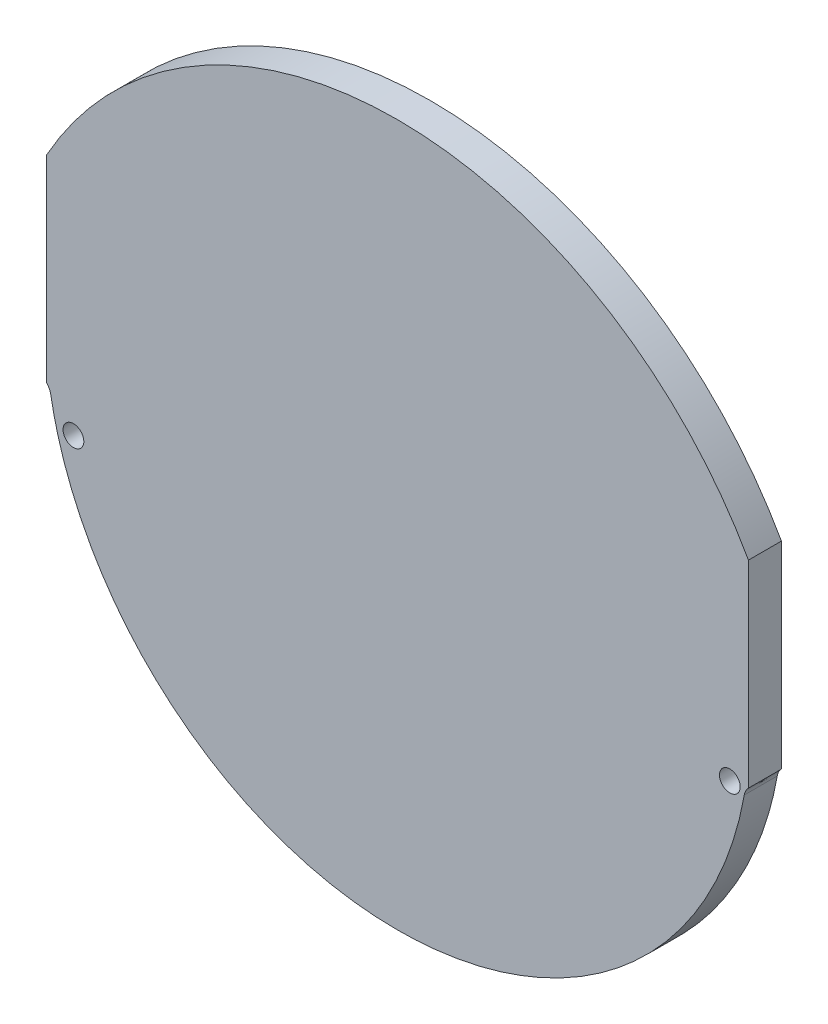
SolidWorks part; units mm, degrees
ref_plane "Front Plane" through (0, 0, 0) normal (0, 0, 1) x (1, 0, 0)
ref_plane "Top Plane" through (0, 0, 0) normal (0, 1, 0) x (1, 0, 0)
ref_plane "Right Plane" through (0, 0, 0) normal (1, 0, 0) x (0, 0, -1)
sketch "Sketch1" plane through (0, 0, 264.79) normal (0, 0, 1) x (1, 0, 0)
  line L4 (33.8, -5.0674) -> (33.8, 13.9555)
  line L5 (-33.8, 13.9555) -> (-33.8, -5.0674)
  line L6 (33.8, -5.0674) -> (33.8, 13.9555)
  line L7 (-33.8, 13.9555) -> (-33.8, -5.0674)
  arc A2 (33.8, 13.9555) -> (-33.8, 13.9555) centre (0, -4.9063) ccw
  arc A3 (33.8, 13.9555) -> (-33.8, 13.9555) centre (0, -4.9063) ccw
  spline S8 degree 3 poles (-1665.2772, 4672.6022) (-1173.4061, 3486.4153) (-275.4153, -82.6719) (6.8422, -33.1229) (8.2789, -32.8049) (9.6992, -32.3906) (10.6425, -32.093) (11.1133, -31.9331) (13.4449, -31.0848) (15.2281, -30.2582) (18.2024, -28.5483) (19.43, -27.7305) (21.0029, -26.5249) (21.3915, -26.2132) (23.2906, -24.6214) (24.6838, -23.2358) (26.8978, -20.6118) (27.7741, -19.4227) (28.8429, -17.7488) (29.1015, -17.3234) (30.3408, -15.181) (31.1764, -13.4031) (32.1933, -10.6392) (32.4924, -9.7015) (52.0357, 62.5776) (-156.4368, 239.9232) (-1760.4572, -4662.5583) knots -18.092209 -18.092209 -18.092209 -18.092209 0.125 0.125 0.1875 0.21875 0.21875 0.25 0.25 0.375 0.375 0.46875 0.46875 0.5 0.5 0.625 0.625 0.71875 0.71875 0.75 0.75 0.875 0.875 0.9375 0.9375 5.607754 5.607754 5.607754 5.607754 only from (0, -33.7996) to (33.3995, -5.839)
  spline S9 degree 3 poles (-4703.662, 1591.5535) (666.3918, -283.7635) (21.7159, -28.3078) (40.8869, 8.7985) (282.5017, -114.1224) (-2521.6975, -4291.9257) knots -86.711245 -86.711245 -86.711245 -86.711245 0.5 0.5 54.695952 54.695952 54.695952 54.695952 only from (33.3995, -5.839) to (33.8, -5.0674)
  spline S10 degree 3 poles (3940.7156, 3019.3454) (-2658.3223, -1737.7647) (-58.7875, 43.2826) (-26.0388, -19.8921) (-275.2587, -149.4952) (-676.0746, 4943.5649) knots -185.189522 -185.189522 -185.189522 -185.189522 0.5 0.5 55.672425 55.672425 55.672425 55.672425 only from (-33.8, -5.0674) to (-33.3995, -5.839)
  spline S11 degree 3 poles (4497.6738, 2082.3439) (769.6171, 587.4932) (-82.3173, 125.886) (-31.5242, -12.4596) (-31.1457, -13.3657) (-30.5182, -14.7033) (-30.299, -15.1456) (-29.8409, -16.0231) (-29.6012, -16.4593) (-28.3592, -18.6074) (-27.2298, -20.2158) (-25.0189, -22.8406) (-23.9959, -23.9044) (-22.5327, -25.2423) (-22.1581, -25.5704) (-20.2608, -27.1617) (-18.6522, -28.2877) (-16.103, -29.7562) (-15.2305, -30.2089) (-13.4403, -31.0408) (-12.5182, -31.4216) (-9.7303, -32.4369) (-7.835, -32.947) (-4.9362, -33.4582) (-3.9606, -33.5863) (71.3988, -40.1195) (208.575, 197.8628) (-4960.1466, 521.9317) knots -9.204623 -9.204623 -9.204623 -9.204623 0.125 0.125 0.1875 0.1875 0.21875 0.21875 0.25 0.25 0.375 0.375 0.46875 0.46875 0.5 0.5 0.625 0.625 0.6875 0.6875 0.75 0.75 0.875 0.875 0.9375 0.9375 5.656684 5.656684 5.656684 5.656684 only from (-33.3995, -5.839) to (0, -33.7996)
  spline S12 degree 3 poles (0, -33.7996) (1.9879, -33.7996) (3.947, -33.6311) (6.8422, -33.1229) (8.2789, -32.8049) (9.6992, -32.3906) (10.6425, -32.093) (11.1133, -31.9331) (13.4449, -31.0848) (15.2281, -30.2582) (18.2024, -28.5483) (19.43, -27.7305) (21.0029, -26.5249) (21.3915, -26.2132) (23.2906, -24.6214) (24.6838, -23.2358) (26.8978, -20.6118) (27.7741, -19.4227) (28.8429, -17.7488) (29.1015, -17.3234) (30.3408, -15.181) (31.1764, -13.4031) (32.1933, -10.6392) (32.4924, -9.7015) (33.0085, -7.7925) (33.2258, -6.819) (33.3995, -5.839) knots 0 0 0 0 0.125 0.125 0.1875 0.21875 0.21875 0.25 0.25 0.375 0.375 0.46875 0.46875 0.5 0.5 0.625 0.625 0.71875 0.71875 0.75 0.75 0.875 0.875 0.9375 0.9375 1 1 1 1
  spline S13 degree 3 poles (33.3995, -5.839) (33.4254, -5.6929) (33.4716, -5.5541) (33.6072, -5.2917) (33.6949, -5.1721) (33.8, -5.0674) knots 0 0 0 0 0.5 0.5 1 1 1 1
  spline S14 degree 3 poles (-33.8, -5.0674) (-33.6949, -5.1721) (-33.6083, -5.29) (-33.4723, -5.5523) (-33.4254, -5.6929) (-33.3995, -5.839) knots 0 0 0 0 0.5 0.5 1 1 1 1
  spline S15 degree 3 poles (-33.3995, -5.839) (-33.0523, -7.7983) (-32.2812, -10.6475) (-31.1457, -13.3657) (-30.5182, -14.7033) (-30.299, -15.1456) (-29.8409, -16.0231) (-29.6012, -16.4593) (-28.3592, -18.6074) (-27.2298, -20.2158) (-25.0189, -22.8406) (-23.9959, -23.9044) (-22.5327, -25.2423) (-22.1581, -25.5704) (-20.2608, -27.1617) (-18.6522, -28.2877) (-16.103, -29.7562) (-15.2305, -30.2089) (-13.4403, -31.0408) (-12.5182, -31.4216) (-9.7303, -32.4369) (-7.835, -32.947) (-4.9362, -33.4582) (-3.9606, -33.5863) (-1.9906, -33.7571) (-0.9946, -33.7996) (0, -33.7996) knots 0 0 0 0 0.125 0.1875 0.1875 0.21875 0.21875 0.25 0.25 0.375 0.375 0.46875 0.46875 0.5 0.5 0.625 0.625 0.6875 0.6875 0.75 0.75 0.875 0.875 0.9375 0.9375 1 1 1 1
  dimension "D1" = 1
extrude "Boss-Extrude1" add sketch "Sketch1" along normal mid plane 3.175
sketch "Sketch2" plane through (0, 0, 266.3775) normal (0, 0, 1) x (1, 0, 0)
  line L4 (23.8, -3.0083) -> (23.8, 11.1446)
  line L5 (-23.8, 11.1446) -> (-23.8, -3.0085)
  line L6 (23.8, -3.0083) -> (23.8, 11.1446)
  line L7 (-23.8, 11.1446) -> (-23.8, -3.0085)
  arc A2 (23.8, -3.0083) -> (23.553, -4.0937) centre (34.8822, -6.101) ccw
  arc A3 (23.8, 11.1446) -> (-23.8, 11.1446) centre (0, -4.9063) ccw
  arc A4 (-23.553, -4.0937) -> (-23.8, -3.0085) centre (-34.8771, -6.1005) ccw
  arc A5 (23.8, -3.0083) -> (23.553, -4.0937) centre (34.8822, -6.101) ccw
  arc A6 (23.8, 11.1446) -> (-23.8, 11.1446) centre (0, -4.9063) ccw
  arc A7 (-23.553, -4.0937) -> (-23.8, -3.0085) centre (-34.8771, -6.1005) ccw
  spline S8 degree 3 poles (2680.94, 1281.8411) (506.3967, 393.8917) (-56.8978, 85.4076) (-22.2288, -8.7611) (-21.9612, -9.3997) (-21.3702, -10.6567) (-21.0461, -11.2774) (-19.9954, -13.0946) (-19.1994, -14.2286) (-17.8623, -15.8137) (-17.3929, -16.3228) (-16.4073, -17.3033) (-15.8889, -17.7769) (-14.2841, -19.123) (-13.1505, -19.9172) (-11.353, -20.9515) (-10.7377, -21.2702) (-9.4752, -21.8559) (-8.825, -22.124) (-6.86, -22.8399) (-5.5242, -23.2005) (-3.4805, -23.5605) (-2.7926, -23.6504) (47.7746, -28.0045) (137.3983, 123.6922) (-2990.4127, 163.3972) knots -8.882699 -8.882699 -8.882699 -8.882699 0.125 0.125 0.1875 0.1875 0.25 0.25 0.375 0.375 0.4375 0.4375 0.5 0.5 0.625 0.625 0.6875 0.6875 0.75 0.75 0.875 0.875 0.9375 0.9375 5.425468 5.425468 5.425468 5.425468 only from (-23.553, -4.0937) to (-0.0002, -23.7996)
  spline S9 degree 3 poles (-43.4673, -2966.6568) (-704.7073, 1985.8538) (-173.6805, -54.6146) (4.8227, -23.3247) (5.4978, -23.1752) (6.8375, -22.8157) (7.5041, -22.6049) (9.4764, -21.8873) (10.7342, -21.3061) (12.5319, -20.2739) (13.1162, -19.9031) (14.2548, -19.1073) (14.8115, -18.6803) (16.4183, -17.3335) (17.4019, -16.3577) (18.741, -14.773) (19.1645, -14.2244) (19.9648, -13.0858) (20.3432, -12.4928) (21.392, -10.6798) (21.9827, -9.4267) (22.7015, -7.4784) (22.9129, -6.8174) (36.0012, 41.5245) (-96.4586, 157.0981) (-998.5334, -2819.8841) knots -16.213795 -16.213795 -16.213795 -16.213795 0.125 0.125 0.1875 0.1875 0.25 0.25 0.375 0.375 0.4375 0.4375 0.5 0.5 0.625 0.625 0.6875 0.6875 0.75 0.75 0.875 0.875 0.9375 0.9375 5.364515 5.364515 5.364515 5.364515 only from (-0.0002, -23.7996) to (23.553, -4.0937)
  spline S10 degree 3 poles (-23.553, -4.0937) (-23.3081, -5.4753) (-22.9455, -6.8144) (-22.2288, -8.7611) (-21.9612, -9.3997) (-21.3702, -10.6567) (-21.0461, -11.2774) (-19.9954, -13.0946) (-19.1994, -14.2286) (-17.8623, -15.8137) (-17.3929, -16.3228) (-16.4073, -17.3033) (-15.8889, -17.7769) (-14.2841, -19.123) (-13.1505, -19.9172) (-11.353, -20.9515) (-10.7377, -21.2702) (-9.4752, -21.8559) (-8.825, -22.124) (-6.86, -22.8399) (-5.5242, -23.2005) (-3.4805, -23.5605) (-2.7926, -23.6504) (-1.4036, -23.77) (-0.7013, -23.7996) (-0.0002, -23.7996) knots 0 0 0 0 0.125 0.125 0.1875 0.1875 0.25 0.25 0.375 0.375 0.4375 0.4375 0.5 0.5 0.625 0.625 0.6875 0.6875 0.75 0.75 0.875 0.875 0.9375 0.9375 1 1 1 1
  spline S11 degree 3 poles (-0.0002, -23.7996) (1.4009, -23.7996) (2.782, -23.6824) (4.8227, -23.3247) (5.4978, -23.1752) (6.8375, -22.8157) (7.5041, -22.6049) (9.4764, -21.8873) (10.7342, -21.3061) (12.5319, -20.2739) (13.1162, -19.9031) (14.2548, -19.1073) (14.8115, -18.6803) (16.4183, -17.3335) (17.4019, -16.3577) (18.741, -14.773) (19.1645, -14.2244) (19.9648, -13.0858) (20.3432, -12.4928) (21.392, -10.6798) (21.9827, -9.4267) (22.7015, -7.4784) (22.9129, -6.8174) (23.2773, -5.4714) (23.4305, -4.7849) (23.553, -4.0937) knots 0 0 0 0 0.125 0.125 0.1875 0.1875 0.25 0.25 0.375 0.375 0.4375 0.4375 0.5 0.5 0.625 0.625 0.6875 0.6875 0.75 0.75 0.875 0.875 0.9375 0.9375 1 1 1 1
  dimension "D1" = 10
sketch "Sketch3" plane through (0, 0, 266.3775) normal (0, 0, 1) x (1, 0, 0)
  circle A1 centre (-31.2161, -8.1644) radius 1
  circle A2 centre (-31.2161, -8.1644) radius 1
  circle A3 centre (32.0093, -5.359) radius 1
  circle A4 centre (32.0093, -5.359) radius 1
  dimension "D1" = 0
  dimension "D2" = 0
extrude "Cut-Extrude2" cut sketch "Sketch3" against normal blind 3.175
